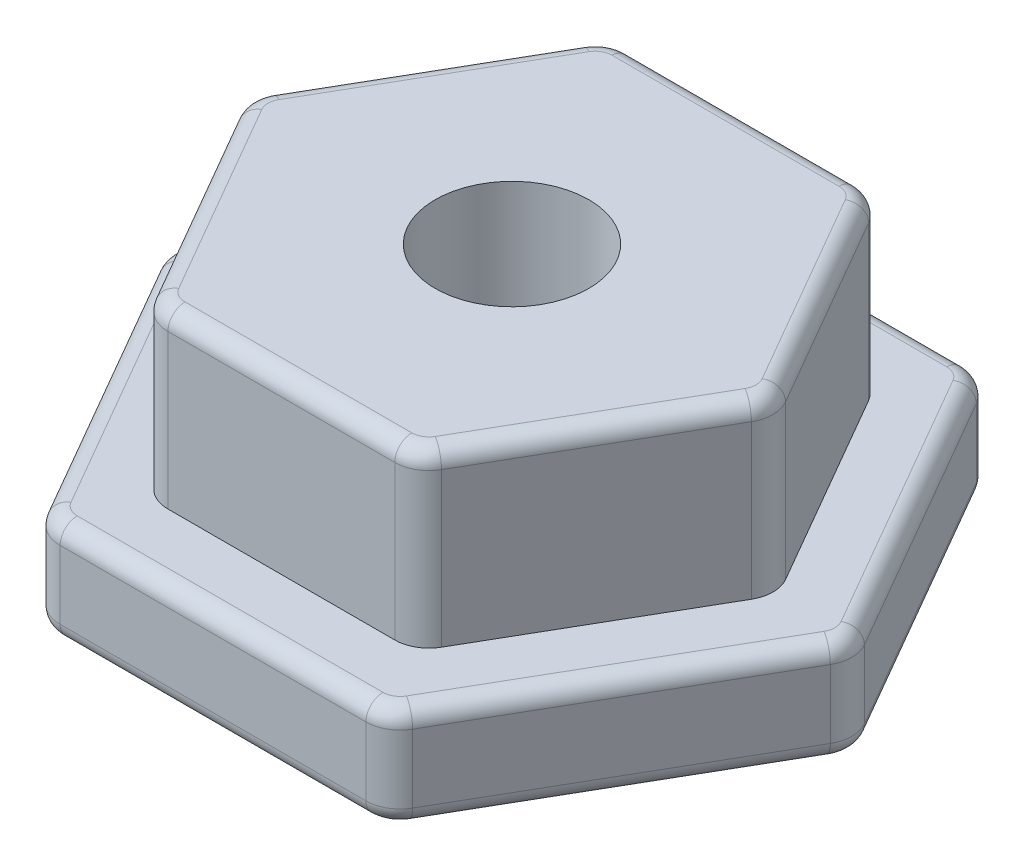
SolidWorks part; units mm, degrees
ref_plane "Front Plane" through (0, 0, 0) normal (0, 0, 1) x (1, 0, 0)
ref_plane "Top Plane" through (0, 0, 0) normal (0, 1, 0) x (1, 0, 0)
ref_plane "Right Plane" through (0, 0, 0) normal (1, 0, 0) x (0, 0, -1)
sketch "Sketch1" plane through (0, 0, 0) normal (0, 1, 0) x (1, 0, 0)
  line L1 (10.1036, 0) -> (5.0518, 8.75)
  line L2 (5.0518, 8.75) -> (-5.0518, 8.75)
  line L3 (-5.0518, 8.75) -> (-10.1036, 0)
  line L4 (-10.1036, 0) -> (-5.0518, -8.75)
  line L5 (-5.0518, -8.75) -> (5.0518, -8.75)
  line L6 (5.0518, -8.75) -> (10.1036, 0)
  circle A0 centre (0, 0) radius 8.75 construction
  dimension "D1" = 17.5
extrude "Boss-Extrude1" add sketch "Sketch1" along normal blind 3
sketch "Sketch2" plane through (0, 3, 0) normal (0, 1, 0) x (1, 0, 0)
  line L1 (3.8971, -6.75) -> (7.7942, 0)
  line L2 (7.7942, 0) -> (3.8971, 6.75)
  line L3 (3.8971, 6.75) -> (-3.8971, 6.75)
  line L4 (-3.8971, 6.75) -> (-7.7942, 0)
  line L5 (-7.7942, 0) -> (-3.8971, -6.75)
  line L6 (-3.8971, -6.75) -> (3.8971, -6.75)
  circle A0 centre (0, 0) radius 6.75 construction
  dimension "D1" = 13.5
extrude "Boss-Extrude2" add sketch "Sketch2" along normal blind 5
sketch "Sketch3" plane through (0, 0, 0) normal (0, -1, 0) x (1, 0, 0)
  point P0 (0, 0)
hole_wizard "CBORE for M4 Pan Head Screw1" positions "Sketch3" profile "Sketch4" counterbore size "M4" standard "ISO" end condition through all
sketch "Sketch4" plane through (0, 0, 0) normal (1, 0, 0) x (0, 0, -1)
  line L0 (0, 0) -> (0, 8)
  line L1 (0, 8) -> (2.25, 8)
  line L3 (2.25, 8) -> (2.25, 3.1)
  line L4 (2.25, 3.1) -> (4.5, 3.1)
  line L5 (4.5, 3.1) -> (4.5, 0)
  line L7 (4.5, 0) -> (0, 0)
  line L11 (0, -6.35) -> (0, 107.95) construction
  dimension "Thru Hole Dia." = 4.5
  dimension "Thru Hole Depth" = 8
  dimension "C'Bore Dia." = 9
  dimension "C'Bore Depth" = 3.1
fillet "Fillet1" radius 1 6 edges at (7.7942, 5.5, 0) (3.8971, 5.5, 6.75) (-3.8971, 5.5, 6.75) (-7.7942, 5.5, 0) (-3.8971, 5.5, -6.75) (3.8971, 5.5, -6.75)
fillet "Fillet2" radius 1 6 edges at (-10.1036, 1.5, 0) (-5.0518, 1.5, -8.75) (5.0518, 1.5, -8.75) (10.1036, 1.5, 0) (5.0518, 1.5, 8.75) (-5.0518, 1.5, 8.75)
fillet "Fillet3" [suppressed] radius 0.5
fillet "Fillet4" [suppressed] radius 0.5
fillet "Fillet5" radius 0.5 12 edges at (-3.8198, 8, 6.616) (-5.8457, 8, 3.375) (-7.6395, 8, 0) (-5.8457, 8, -3.375) (-3.8198, 8, -6.616) (0, 8, -6.75) (3.8198, 8, -6.616) (5.8457, 8, -3.375) (7.6395, 8, 0) (5.8457, 8, 3.375) (3.8198, 8, 6.616) (0, 8, 6.75)
fillet "Fillet6" radius 0.5 13 edges at (-4.9745, 0, 8.616) (0, 0, 8.75) (4.9745, 0, 8.616) (7.5777, 0, 4.375) (9.9489, 0, 0) (7.5777, 0, -4.375) (4.9745, 0, -8.616) (0, 0, -8.75) (-4.9745, 0, -8.616) (-7.5777, 0, -4.375) (-9.9489, 0, 0) (-7.5777, 0, 4.375) (0, 0, -4.5)
fillet "Fillet7" radius 0.5 12 edges at (4.9745, 3, -8.616) (7.5777, 3, -4.375) (9.9489, 3, 0) (7.5777, 3, 4.375) (4.9745, 3, 8.616) (0, 3, 8.75) (-4.9745, 3, 8.616) (-7.5777, 3, 4.375) (-9.9489, 3, 0) (-7.5777, 3, -4.375) (-4.9745, 3, -8.616) (0, 3, -8.75)
